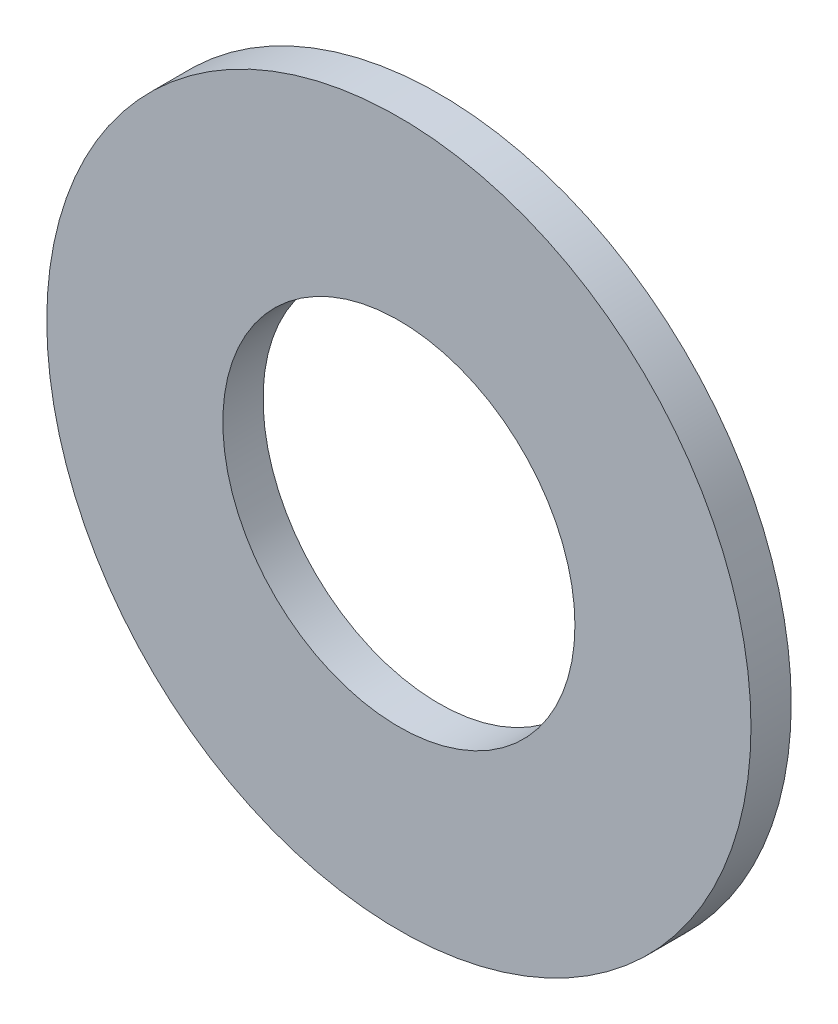
SolidWorks part; units mm, degrees
ref_plane "Front Plane" through (0, 0, 0) normal (0, 0, 1) x (1, 0, 0)
ref_plane "Top Plane" through (0, 0, 0) normal (0, 1, 0) x (1, 0, 0)
ref_plane "Right Plane" through (0, 0, 0) normal (1, 0, 0) x (0, 0, -1)
sketch "Sketch1" plane through (0, 0, 0) normal (0, 0, 1) x (1, 0, 0)
  circle A0 centre (0, 0) radius 1.75
  circle A1 centre (0, 0) radius 3.5
  dimension "D1" = 3.5
  dimension "D2" = 7
extrude "Boss-Extrude1" add sketch "Sketch1" along normal blind 0.4
